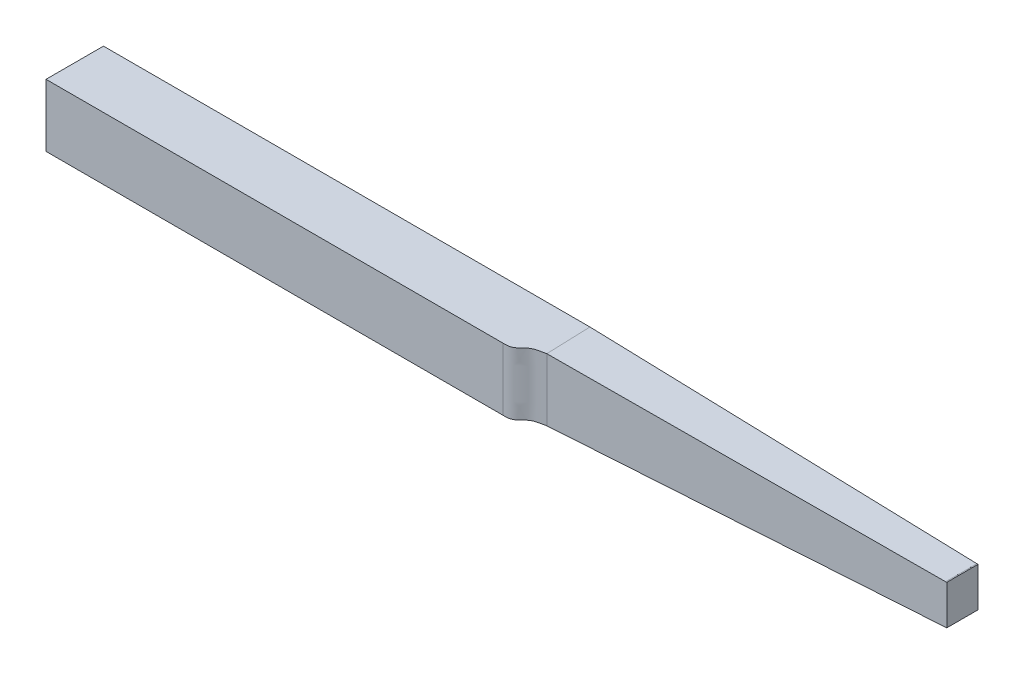
SolidWorks part; units mm, degrees
ref_plane "Alzado" through (0, 0, 0) normal (1, 0, 0) x (0, 1, 0)
ref_plane "Planta" through (0, 0, 0) normal (0, 0, 1) x (0, 1, 0)
ref_plane "Vista lateral" through (0, 0, 0) normal (0, 1, 0) x (-1, 0, 0)
sketch "Croquis1" plane through (0, 0, 0) normal (0, 1, 0) x (-1, 0, 0)
  line L0 (-558.4836, 0) -> (652.636, 0) construction
  line L1 (-560, 36.8) -> (560, 36.8)
  line L2 (-560, 36.8) -> (-560, -36.8)
  line L3 (-560, -36.8) -> (560, -36.8)
  line L4 (560, 36.8) -> (560, -36.8)
  line L5 (-560, 36.8) -> (560, -36.8) construction
  line L6 (-560, -36.8) -> (560, 36.8) construction
  point P0 (0, 0)
  dimension "D1" = 73.6
  dimension "D2" = 1120
extrude "Saliente-Extruir2" add sketch "Croquis1" along normal blind 80
sketch "Croquis3" plane through (0, 80, 0) normal (0, 1, 0) x (-1, 0, 0)
  line L0 (-25, 36.8) -> (-25, -36.8) construction
  line L3 (560, 36.8) -> (-560, 36.8) construction
  line L4 (-560, -36.8) -> (560, -36.8) construction
  line L5 (-560, 36.8) -> (-560, -36.8) construction
  line L6 (-65, 36.8) -> (-65, -36.8) construction
  line L7 (175, 36.8) -> (175, -36.8) construction
  line L8 (475, 36.8) -> (475, -36.8) construction
  line L9 (532, 36.8) -> (532, -36.8) construction
  line L10 (-560, 3.2) -> (-65, 20.4)
  line L11 (-65, 36.8) -> (-65, 20.4)
  line L12 (-65, 36.8) -> (-560, 36.8)
  dimension "D1" = 535
  dimension "D2" = 40
  dimension "D3" = 200
  dimension "D4" = 300
  dimension "D5" = 57
  dimension "D6" = 40
  dimension "D7" = 57.2
extrude "Cortar-Extruir1" cut sketch "Croquis3" against normal blind 80 and the other way through all
sketch "Croquis5" plane through (0, 80, 0) normal (0, 1, 0) x (-1, 0, 0)
  line L0 (-25, 36.8) -> (-25, -36.8) construction
  line L1 (560, 36.8) -> (-65, 36.8) construction
  line L2 (-560, -36.8) -> (560, -36.8) construction
  line L3 (-65, 20.4) -> (-65, 36.8) construction
  line L4 (-25, 36.8) -> (-8.2536, 36.8)
  line L5 (-65, 20.4) -> (-65, 36.8)
  line L6 (-65, 36.8) -> (-25, 36.8)
  spline S0 degree 3 poles (-65, 20.4) (-56.7842, 22.1076) (-47.8188, 23.3374) (-39.843, 33.5861) (-32.9878, 36.6311) (-31.1757, 36.8) (-25, 36.8) knots 0 0 0 0 0.42265 0.727848 0.789398 1 1 1 1
  dimension "D1" = 40
extrude "Cortar-Extruir2" cut sketch "Croquis5" against normal blind 80 contours S0 L5 L6
sketch "Croquis6" plane through (0.7864, 0, 22.6313) normal (0.0347, 0, 0.9994) x (0.9994, 0, -0.0347)
  line L2 (64.2524, 0) -> (559.5511, 0)
  line L5 (64.2524, 0) -> (559.5511, 14.75)
  line L7 (559.5511, 80) -> (559.5511, 0) construction
  line L8 (559.5511, 14.75) -> (559.5511, 0)
  dimension "D1" = 14.75
extrude "Cortar-Extruir6" cut sketch "Croquis6" against normal blind 80
sketch "Croquis9" plane through (0, 0, -36.8) normal (0, 0, -1) x (1, 0, 0)
  line L0 (558.6101, 0) -> (560, 0)
  line L1 (558.6101, -14.75) -> (560, -14.75)
  line L2 (560, -14.75) -> (560, 0)
  line L3 (558.6101, 0) -> (558.6101, -14.75)
extrude "Cortar-Extruir7" cut sketch "Croquis9" against normal blind 80
sketch "Croquis10" plane through (0.7864, 0, 22.6313) normal (0.0347, 0, 0.9994) x (0.9994, 0, -0.0347)
  line L0 (64.2524, 80) -> (559.5511, 65.25)
  line L2 (559.5511, 80) -> (559.5511, 14.75) construction
  line L3 (559.5511, 65.25) -> (559.5511, 80)
  line L4 (559.5511, 80) -> (64.2524, 80)
  dimension "D1" = 14.75
extrude "Cortar-Extruir11" cut sketch "Croquis10" against normal blind 80
sketch "Croquis11" plane through (0, 0, -36.8) normal (0, 0, -1) x (1, 0, 0)
  line L0 (558.6101, -65.25) -> (560, -65.25)
  line L1 (560, -65.25) -> (560, -80)
  line L2 (560, -80) -> (558.6101, -80)
  line L3 (558.6101, -80) -> (558.6101, -65.25)
extrude "Cortar-Extruir12" cut sketch "Croquis11" against normal blind 80
